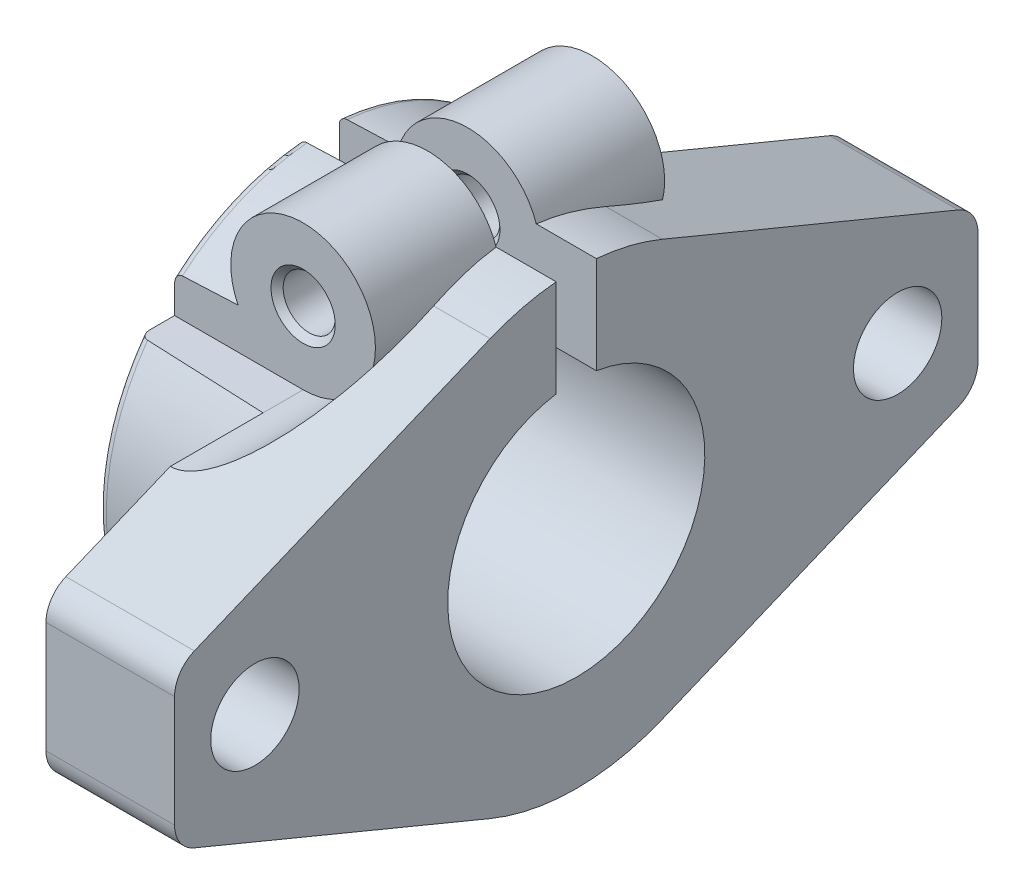
SolidWorks part; units mm, degrees
ref_plane "前基準面" through (0, 0, 0) normal (0, 0, 1) x (1, 0, 0)
ref_plane "上基準面" through (0, 0, 0) normal (0, 1, 0) x (1, 0, 0)
ref_plane "右基準面" through (0, 0, 0) normal (1, 0, 0) x (0, 0, -1)
ref_plane "平面1" through (0, 0, 0) normal (1, 0, 0) x (0, 0, -1)
sketch "草圖1" plane through (0, 0, 0) normal (1, 0, 0) x (0, 0, -1)
  line L0 (-25, 3.4618) -> (-25, -3.4618)
  line L1 (-23.7654, -5.3096) -> (-5.3576, -12.9343)
  line L2 (5.3576, -12.9343) -> (23.7654, -5.3096)
  line L3 (25, -3.4618) -> (25, 3.4618)
  line L4 (23.7654, 5.3096) -> (5.3576, 12.9343)
  line L5 (-5.3576, 12.9343) -> (-23.7654, 5.3096)
  arc A0 (-25, -3.4618) -> (-23.7654, -5.3096) centre (-23, -3.4618) ccw
  arc A1 (-5.3576, -12.9343) -> (0, -14) centre (0, 0) ccw
  arc A2 (0, -14) -> (5.3576, -12.9343) centre (0, 0) ccw
  arc A3 (23.7654, -5.3096) -> (25, -3.4618) centre (23, -3.4618) ccw
  arc A4 (25, 3.4618) -> (23.7654, 5.3096) centre (23, 3.4618) ccw
  arc A5 (5.3576, 12.9343) -> (0, 14) centre (0, 0) ccw
  arc A6 (0, 14) -> (-5.3576, 12.9343) centre (0, 0) ccw
  arc A7 (-23.7654, 5.3096) -> (-25, 3.4618) centre (-23, 3.4618) ccw
extrude "填料-伸長1" add sketch "草圖1" against normal blind 8
ref_plane "平面2" through (0, 0, 0) normal (0, 0, 1) x (1, 0, 0)
sketch "草圖2" plane through (0, 0, 0) normal (0, 0, 1) x (1, 0, 0)
  line L0 (-16, 0) -> (-16, 13.2301)
  line L1 (-15.5097, 13.7378) -> (-8, 14)
  line L2 (-8, 14) -> (-8, 0)
  line L3 (-8, 0) -> (-16, 0)
  line L4 (-8, 0) -> (-16, 0) construction
  arc A0 (-16, 13.2301) -> (-15.5097, 13.7378) centre (-15.492, 13.2301) cw
revolve "旋轉1" add sketch "草圖2" angle 360 about L4
ref_plane "平面3" through (0, 0, 0) normal (0, 0, 1) x (1, 0, 0)
sketch "草圖3" plane through (0, 0, 0) normal (0, 0, 1) x (1, 0, 0)
  circle A0 centre (-8, 12.5) radius 4.5
extrude "填料-伸長2" add sketch "草圖3" against normal blind 9 and the other way blind 9
ref_plane "平面4" through (0, 0, 9) normal (0, 0, 1) x (1, 0, 0)
sketch "草圖4" plane through (0, 0, 9) normal (0, 0, 1) x (1, 0, 0)
  line L0 (-16, 8) -> (-8, 8)
  line L1 (-12.5, 12.5) -> (-16, 12.5)
  line L2 (-16, 12.5) -> (-16, 8)
  arc A0 (-8, 8) -> (-12.5, 12.5) centre (-8, 12.5) ccw
extrude "除料-伸長1" cut sketch "草圖4" along normal blind 9
ref_plane "平面5" through (0, 0, 0) normal (1, 0, 0) x (0, 0, -1)
sketch "草圖5" plane through (0, 0, 0) normal (1, 0, 0) x (0, 0, -1)
  line L0 (-1.25, 0) -> (1.25, 0)
  line L1 (1.25, 0) -> (1.25, 31)
  line L2 (1.25, 31) -> (-1.25, 31)
  line L3 (-1.25, 31) -> (-1.25, 0)
extrude "除料-伸長2" cut sketch "草圖5" against normal blind 16
ref_plane "平面6" through (0, 0, 0) normal (0, 0, 1) x (1, 0, 0)
sketch "草圖6" plane through (0, 0, 0) normal (0, 0, 1) x (1, 0, 0)
  line L0 (-16, 0) -> (-16, 10)
  line L1 (-16, 10) -> (-14, 10)
  line L2 (-14, 10) -> (-14, 8)
  line L3 (-14, 8) -> (0, 8)
  line L4 (0, 8) -> (0, 0)
  line L5 (0, 0) -> (-16, 0)
  line L6 (0, 0) -> (-16, 0) construction
revolve "除料-旋轉1" cut sketch "草圖6" angle 360 about L6
ref_plane "平面7" through (-8, 0, 0) normal (1, 0, 0) x (0, 0, -1)
sketch "草圖7" plane through (-8, 0, 0) normal (1, 0, 0) x (0, 0, -1)
  line L0 (1.25, 12.5) -> (1.25, 14.5)
  line L1 (1.25, 14.5) -> (1.629, 14.121)
  line L2 (1.629, 14.121) -> (8.621, 14.121)
  line L3 (8.621, 14.121) -> (9.1, 14.6)
  line L4 (9.1, 14.6) -> (13.5, 14.6)
  line L5 (13.5, 14.6) -> (13.5, 12.5)
  line L6 (13.5, 12.5) -> (1.25, 12.5)
  line L7 (13.5, 12.5) -> (1.25, 12.5) construction
revolve "除料-旋轉2" cut sketch "草圖7" angle 360 about L7
cosmetic thread "裝飾螺紋線1" parameters "D1"=7.75, "D2"=4
ref_plane "平面8" through (-8, 0, 0) normal (1, 0, 0) x (0, 0, -1)
sketch "草圖8" plane through (-8, 0, 0) normal (1, 0, 0) x (0, 0, -1)
  line L0 (-9, 12.5) -> (-9, 14.5)
  line L1 (-9, 14.5) -> (-8.621, 14.121)
  line L2 (-8.621, 14.121) -> (-1.629, 14.121)
  line L3 (-1.629, 14.121) -> (-1.25, 14.5)
  line L4 (-1.25, 14.5) -> (-1.25, 12.5)
  line L5 (-1.25, 12.5) -> (-9, 12.5)
  line L6 (-1.25, 12.5) -> (-9, 12.5) construction
revolve "除料-旋轉3" cut sketch "草圖8" angle 360 about L6
cosmetic thread "裝飾螺紋線2" parameters "D1"=7.75, "D2"=4
ref_plane "平面9" through (0, 0, 0) normal (1, 0, 0) x (0, 0, -1)
sketch "草圖9" plane through (0, 0, 0) normal (1, 0, 0) x (0, 0, -1)
  circle A0 centre (20, 0) radius 2.75
extrude "除料-伸長3" cut sketch "草圖9" against normal blind 8
ref_plane "平面10" through (0, 0, 0) normal (1, 0, 0) x (0, 0, -1)
sketch "草圖10" plane through (0, 0, 0) normal (1, 0, 0) x (0, 0, -1)
  circle A0 centre (-20, 0) radius 2.75
extrude "除料-伸長4" cut sketch "草圖10" against normal blind 8
